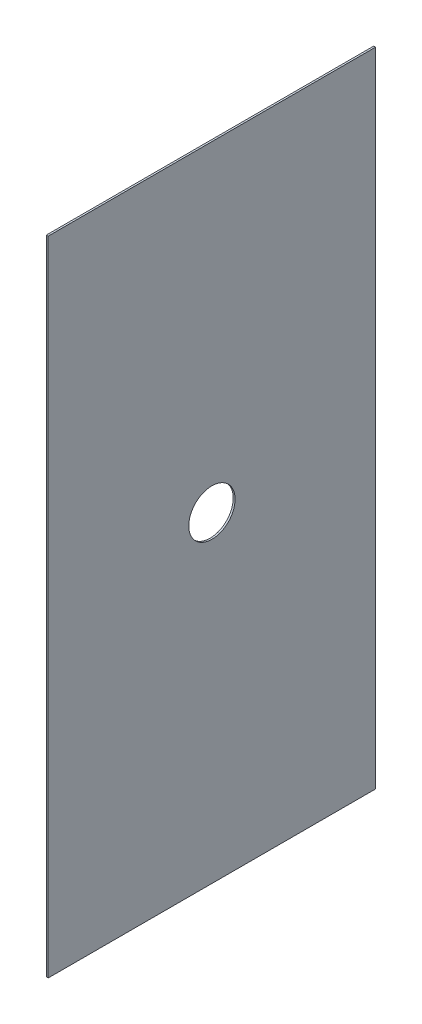
SolidWorks part; units mm, degrees
ref_plane "Alzado" through (0, 0, 0) normal (0, 0, 1) x (1, 0, 0)
ref_plane "Planta" through (0, 0, 0) normal (0, 1, 0) x (1, 0, 0)
ref_plane "Vista lateral" through (0, 0, 0) normal (1, 0, 0) x (0, 0, -1)
sketch "Croquis1" plane through (0, 0, 0) normal (1, 0, 0) x (0, -1, 0)
  line L1 (520, -265) -> (-520, -265)
  line L2 (520, -265) -> (520, 265)
  line L3 (520, 265) -> (-520, 265)
  line L4 (-520, -265) -> (-520, 265)
  line L5 (520, -265) -> (-520, 265) construction
  line L6 (520, 265) -> (-520, -265) construction
  point P0 (0, 0)
  dimension "D1" = 530
  dimension "D2" = 1040
extrude "Extruir1" add sketch "Croquis1" along normal blind 3
sketch "Croquis2" plane through (3, 0, 0) normal (1, 0, 0) x (0, 0, -1)
  line L0 (0, 520) -> (0, -520) construction
  line L1 (265, 520) -> (-265, 520) construction
  line L2 (-265, -520) -> (265, -520) construction
  circle A0 centre (0, 0) radius 37.5
  dimension "D1" = 75
extrude "Extruir2" cut sketch "Croquis2" against normal through all
